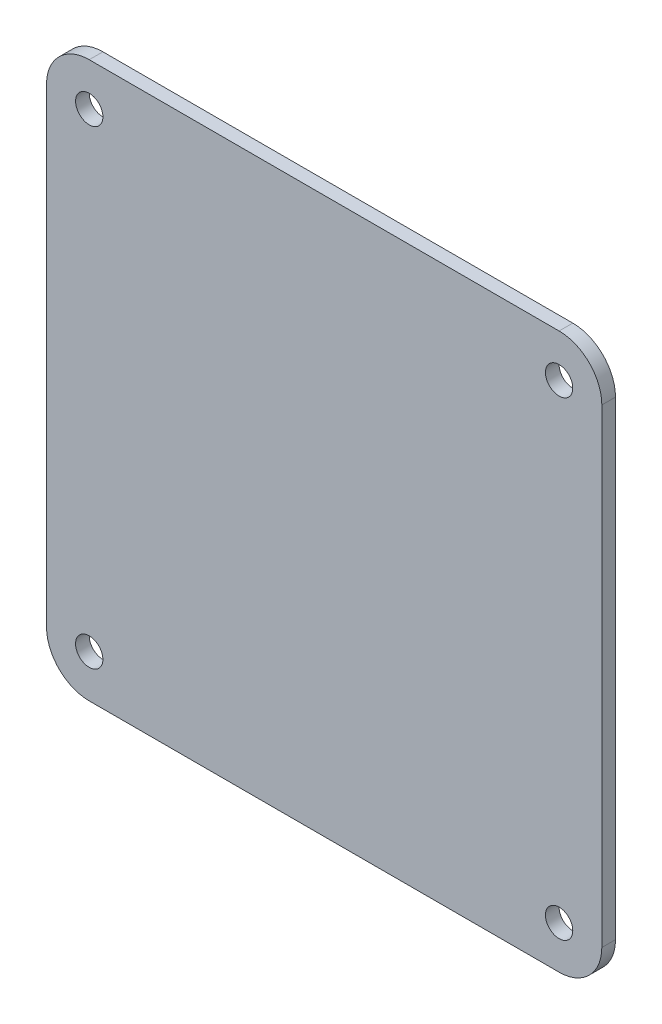
SolidWorks part; units mm, degrees
ref_plane "正面" through (0, 0, 0) normal (0, 0, 1) x (1, 0, 0)
ref_plane "平面" through (0, 0, 0) normal (0, 1, 0) x (1, 0, 0)
ref_plane "右側面" through (0, 0, 0) normal (1, 0, 0) x (0, 0, -1)
sketch "ｽｹｯﾁ1" plane through (0, 0, 0) normal (0, 0, 1) x (1, 0, 0)
  line L0 (0, 39.4647) -> (0, -40.1225) construction
  line L1 (32.5, -32.5) -> (-32.5, -32.5)
  line L2 (32.5, -32.5) -> (32.5, 32.5)
  line L3 (32.5, 32.5) -> (-32.5, 32.5)
  line L4 (-32.5, -32.5) -> (-32.5, 32.5)
  line L5 (32.5, -32.5) -> (-32.5, 32.5) construction
  line L6 (32.5, 32.5) -> (-32.5, -32.5) construction
  line L7 (-49.5505, 0) -> (46.4847, 0) construction
  circle A0 centre (-27.5, 27.5) radius 1.6
  circle A1 centre (27.5, 27.5) radius 1.6
  circle A2 centre (-27.5, -27.5) radius 1.6
  circle A3 centre (27.5, -27.5) radius 1.6
  point P0 (0, 0)
  dimension "D3" = 3.2
  dimension "D1" = 65
  dimension "D2" = 65
  dimension "D4" = 5
extrude "ﾎﾞｽ - 押し出し1" add sketch "ｽｹｯﾁ1" along normal blind 1.6
fillet "ﾌｨﾚｯﾄ1" radius 5 4 edges at (-32.5, -32.5, 0.8) (32.5, -32.5, 0.8) (-32.5, 32.5, 0.8) (32.5, 32.5, 0.8)
